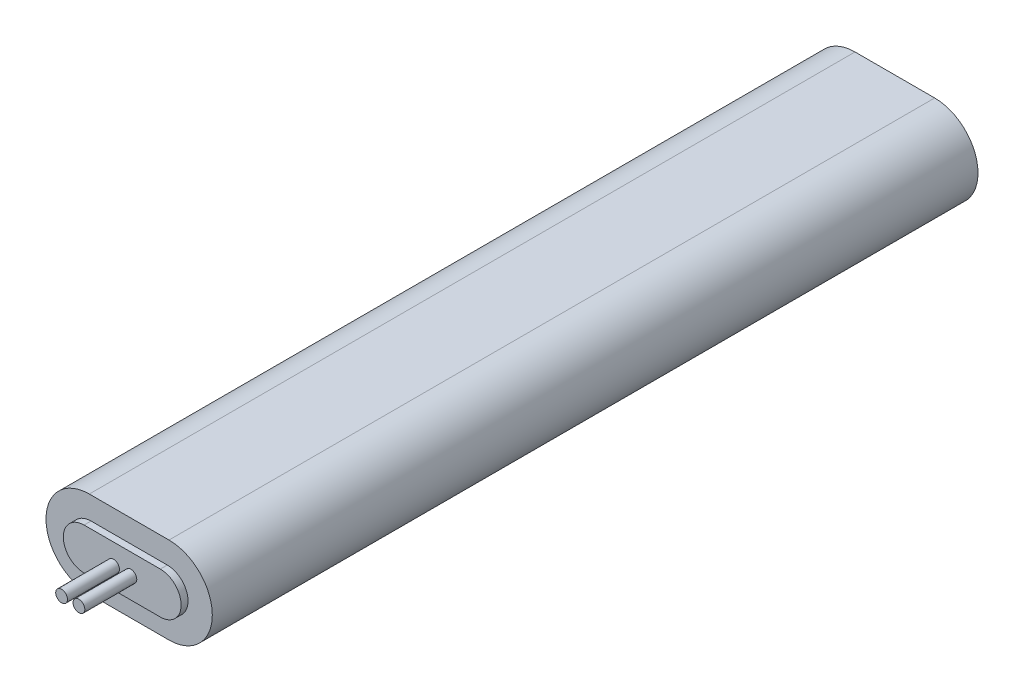
SolidWorks part; units mm, degrees
other "Marquage1"
sketch "Esquisse4"
sketch "Esquisse5" plane through (-24, 12.5, 127.5) normal (-0.0815, 0.4376, 0.8955) x (0.9925, -0.0461, 0.1128)
ref_plane "Plan de face" through (0, 0, 0) normal (0, 0, 1) x (1, 0, 0)
ref_plane "Plan de dessus" through (0, 0, 0) normal (0, 1, 0) x (1, 0, 0)
ref_plane "Plan de droite" through (0, 0, 0) normal (1, 0, 0) x (0, 0, -1)
sketch "Esquisse1" plane through (0, 0, 0) normal (0, 0, 1) x (1, 0, 0)
  line L0 (0, 12.5) -> (0, -12.5) construction
  line L1 (-11.5, 12.5) -> (11.5, 12.5)
  line L3 (-11.5, -12.5) -> (11.5, -12.5)
  arc A1 (11.5, -12.5) -> (11.5, 12.5) centre (11.5, 0) ccw
  arc A2 (-11.5, 12.5) -> (-11.5, -12.5) centre (-11.5, 0) ccw
  point P6 (-24, 0)
  point P7 (24, 0)
  dimension "D2" = 48
  dimension "D1" = 25
extrude "Boss.-Extru.1" add sketch "Esquisse1" along normal mid plane 221
sketch "Esquisse2" plane through (0, 0, 110.5) normal (0, 0, 1) x (1, 0, 0)
  line L0 (-11, 0) -> (11, 0) construction
  line L1 (-11, 6) -> (11, 6)
  line L2 (-11, -6) -> (11, -6)
  arc A0 (-11, 6) -> (-11, -6) centre (-11, 0) ccw
  arc A1 (11, -6) -> (11, 6) centre (11, 0) ccw
  point P2 (0, 0)
  point P8 (17, 0)
  point P9 (-17, 0)
  dimension "D1" = 12
  dimension "D2" = 34
extrude "Boss.-Extru.2" add sketch "Esquisse2" along normal blind 2
sketch "Esquisse3" plane through (0, 0, 112.5) normal (0, 0, 1) x (1, 0, 0)
  line L0 (0, 0) -> (0, 6) construction
  line L1 (11, 6) -> (-11, 6) construction
  line L2 (2.5, 0) -> (0, 0) construction
  circle A0 centre (2.5, 0) radius 1.7
  circle A1 centre (-2.5, 0) radius 1.7
  dimension "D1" = 3.4
  dimension "D2" = 5
extrude "Boss.-Extru.3" add sketch "Esquisse3" along normal blind 15
